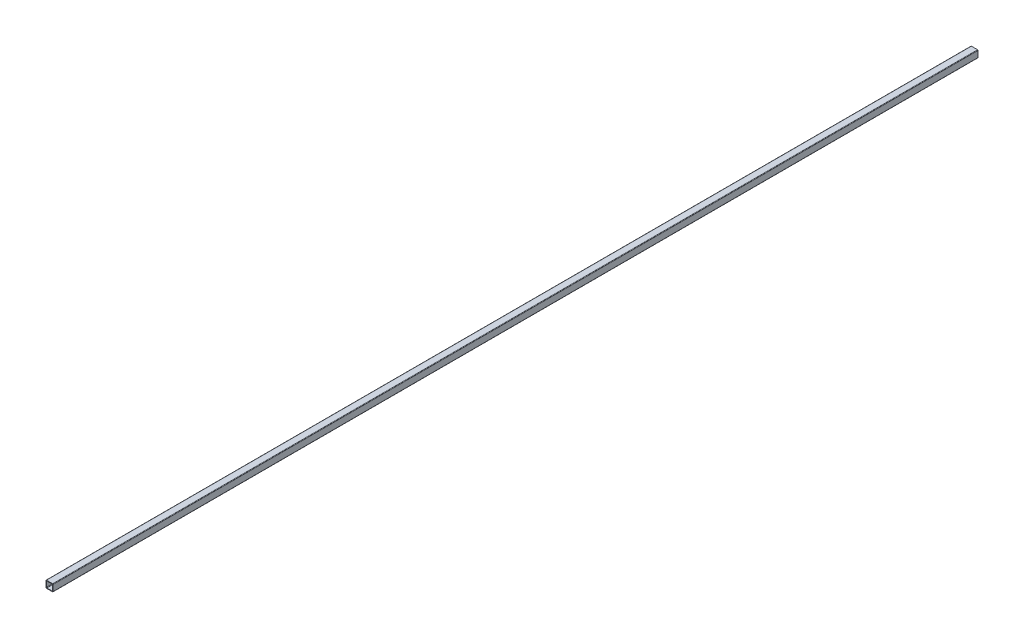
SolidWorks part; units mm, degrees
material "ASTM A500 Grade B"
ref_plane "Front Plane" through (0, 0, 0) normal (0, 0, 1) x (1, 0, 0)
ref_plane "Top Plane" through (0, 0, 0) normal (0, 1, 0) x (1, 0, 0)
ref_plane "Right Plane" through (0, 0, 0) normal (1, 0, 0) x (0, 0, -1)
sketch "Sketch1" plane through (0, 0, 0) normal (0, 0, 1) x (1, 0, 0)
  line L0 (5.3086, -2.7686) -> (32.7914, -2.7686)
  line L1 (2.54, 0) -> (35.56, 0)
  line L2 (0, -2.54) -> (0, -35.56)
  line L3 (2.54, -38.1) -> (35.56, -38.1)
  line L4 (38.1, -2.54) -> (38.1, -35.56)
  line L5 (35.3314, -5.3086) -> (35.3314, -32.7914)
  line L6 (5.3086, -35.3314) -> (32.7914, -35.3314)
  line L7 (2.7686, -5.3086) -> (2.7686, -32.7914)
  line L8 (0, 0) -> (0, -38.1) construction
  line L9 (0, -38.1) -> (38.1, -38.1) construction
  line L10 (38.1, 0) -> (38.1, -38.1) construction
  line L11 (2.7686, -2.7686) -> (2.7686, -35.3314) construction
  line L12 (2.7686, -35.3314) -> (35.3314, -35.3314) construction
  line L13 (35.3314, -2.7686) -> (35.3314, -35.3314) construction
  line L14 (2.7686, -2.7686) -> (35.3314, -2.7686) construction
  line L15 (0, 0) -> (38.1, 0) construction
  arc A0 (0, -35.56) -> (2.54, -38.1) centre (2.54, -35.56) ccw
  arc A1 (38.1, -35.56) -> (35.56, -38.1) centre (35.56, -35.56) cw
  arc A2 (2.7686, -32.7914) -> (5.3086, -35.3314) centre (5.3086, -32.7914) ccw
  arc A3 (32.7914, -35.3314) -> (35.3314, -32.7914) centre (32.7914, -32.7914) ccw
  arc A4 (35.3314, -5.3086) -> (32.7914, -2.7686) centre (32.7914, -5.3086) ccw
  arc A5 (38.1, -2.54) -> (35.56, 0) centre (35.56, -2.54) ccw
  arc A6 (0, -2.54) -> (2.54, 0) centre (2.54, -2.54) cw
  arc A7 (5.3086, -2.7686) -> (2.7686, -5.3086) centre (5.3086, -5.3086) ccw
  point P12 (0, -38.1)
  dimension "D4" = 2.54
  dimension "D3" = 2.7686
extrude "Boss-Extrude1" add sketch "Sketch1" along normal blind 5000
fillet "Fillet1" [suppressed] radius 1
